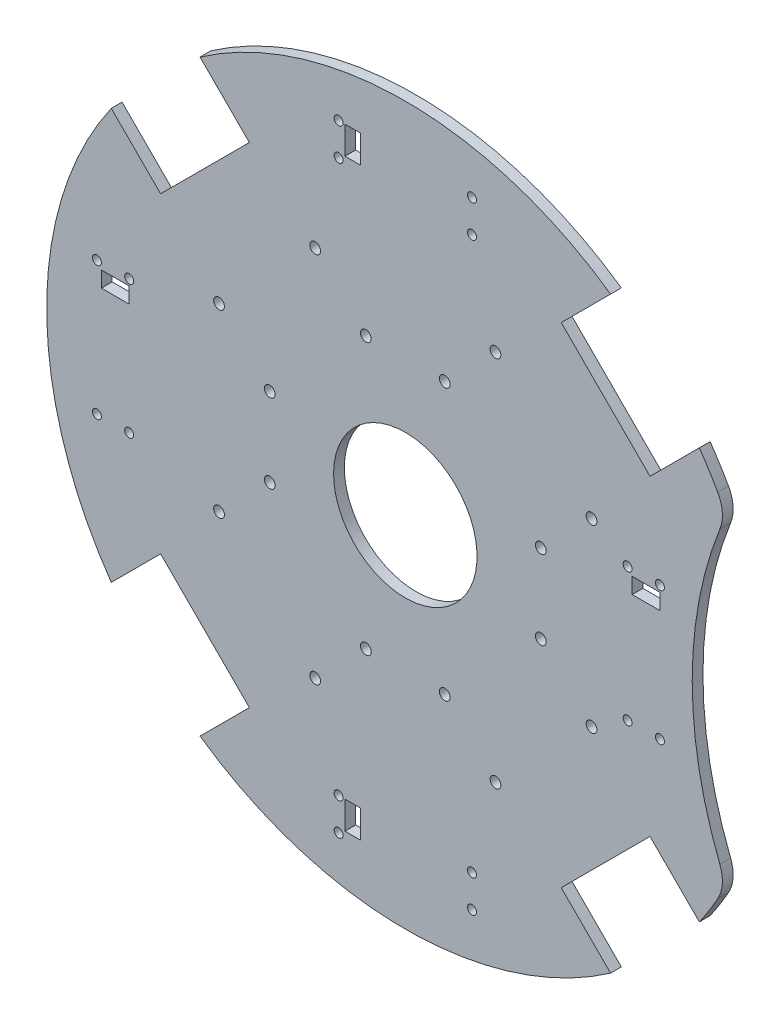
SolidWorks part; units mm, degrees
ref_plane "Alzado" through (0, 0, 0) normal (0, 0, 1) x (1, 0, 0)
ref_plane "Planta" through (0, 0, 0) normal (0, 1, 0) x (1, 0, 0)
ref_plane "Vista lateral" through (0, 0, 0) normal (1, 0, 0) x (0, 0, -1)
sketch "Croquis1" plane through (0, 0, 0) normal (0, 0, 1) x (1, 0, 0)
  circle A0 centre (0, 0) radius 100
  dimension "D1" = 200
extrude "Saliente-Extruir1" add sketch "Croquis1" along normal blind 3
sketch "Croquis3" plane through (0, 0, 3) normal (0, 0, 1) x (1, 0, 0)
  line L0 (0, 0) -> (190, 0) construction
  circle A0 centre (190, 0) radius 110
  dimension "D1" = 220
  dimension "D2" = 190
extrude "Cortar-Extruir1" cut sketch "Croquis3" against normal blind 3
fillet "Redondeo1" radius 10 2 edges at (89.4737, -44.6594, 1.5) (89.4737, 44.6594, 1.5)
sketch "Croquis4" plane through (0, 0, 3) normal (0, 0, 1) x (1, 0, 0)
  line L0 (-83.085, -58.3363) -> (-58.3363, -83.085)
  line L1 (-83.085, -58.3363) -> (-68.2358, -43.4871)
  line L2 (0, -100) -> (-100, 0) construction
  line L3 (-70.7107, -70.7107) -> (-38.5373, -38.5373) construction
  line L4 (-38.5373, -38.5373) -> (-25.1376, -51.937) construction
  line L5 (-38.5373, -38.5373) -> (-51.937, -25.1376) construction
  line L6 (-25.1376, -51.937) -> (-10.9955, -37.7949) construction
  line L7 (-51.937, -25.1376) -> (-37.7949, -10.9955) construction
  line L8 (-68.2358, -43.4871) -> (-43.4871, -68.2358)
  line L9 (-58.3363, -83.085) -> (-43.4871, -68.2358)
  line L10 (-58.3363, 83.085) -> (-43.4871, 68.2358)
  line L11 (-43.4871, 68.2358) -> (-68.2358, 43.4871)
  line L12 (-83.085, 58.3363) -> (-68.2358, 43.4871)
  line L13 (-58.3363, 83.085) -> (-83.085, 58.3363)
  line L14 (83.085, 58.3363) -> (68.2358, 43.4871)
  line L15 (68.2358, 43.4871) -> (43.4871, 68.2358)
  line L16 (58.3363, 83.085) -> (43.4871, 68.2358)
  line L17 (83.085, 58.3363) -> (58.3363, 83.085)
  line L18 (58.3363, -83.085) -> (43.4871, -68.2358)
  line L19 (43.4871, -68.2358) -> (68.2358, -43.4871)
  line L20 (83.085, -58.3363) -> (68.2358, -43.4871)
  line L21 (58.3363, -83.085) -> (83.085, -58.3363)
  arc A0 (87.1345, 49.0671) -> (87.1345, -49.0671) centre (0, 0) ccw construction
  circle A1 centre (-10.9955, 37.7949) radius 1.5
  circle A2 centre (-51.937, -25.1376) radius 1.5
  circle A3 centre (-25.1376, -51.937) radius 1.5
  circle A4 centre (-10.9955, -37.7949) radius 1.5
  circle A5 centre (-37.7949, -10.9955) radius 1.5
  circle A6 centre (-37.7949, 10.9955) radius 1.5
  circle A7 centre (-51.937, 25.1376) radius 1.5
  circle A8 centre (-25.1376, 51.937) radius 1.5
  circle A9 centre (37.7949, 10.9955) radius 1.5
  circle A10 centre (10.9955, 37.7949) radius 1.5
  circle A11 centre (25.1376, 51.937) radius 1.5
  circle A12 centre (51.937, 25.1376) radius 1.5
  circle A13 centre (10.9955, -37.7949) radius 1.5
  circle A14 centre (37.7949, -10.9955) radius 1.5
  circle A15 centre (51.937, -25.1376) radius 1.5
  circle A16 centre (25.1376, -51.937) radius 1.5
  point P43 (0, 0)
  point P60 (0, 0)
  dimension "D1" = 3
  dimension "D2" = 3
  dimension "D3" = 3
  dimension "D4" = 3
  dimension "D5" = 20
  dimension "D6" = 20
  dimension "D7" = 37.9
  dimension "D8" = 4
  dimension "D9" = 57.7005
  dimension "D10" = 35
  dimension "D11" = 21
  dimension "D12" = 35
  dimension "D13" = 17.5
  dimension "D14" = 79
  dimension "D15" = 4
extrude "Cortar-Extruir2" cut sketch "Croquis4" against normal through all
sketch "Croquis5" plane through (0, 0, 3) normal (0, 0, 1) x (1, 0, 0)
  line L0 (-100, 0) -> (-88, 0) construction
  line L1 (0, 0) -> (0, -100) construction
  line L2 (0, 0) -> (0, 100) construction
  line L3 (20.59, 88) -> (20.59, 75) construction
  line L4 (-88, 20.59) -> (-88, -20.59) construction
  line L5 (-20.59, -88) -> (20.59, -88) construction
  line L6 (-88, 20.59) -> (-75, 20.59) construction
  line L7 (-75, 20.59) -> (-75, -20.59) construction
  line L8 (-75, -20.59) -> (-88, -20.59) construction
  line L9 (20.59, 75) -> (-20.59, 75) construction
  line L10 (-20.59, 88) -> (20.59, 88) construction
  line L11 (60, 20.59) -> (60, -20.59) construction
  line L12 (-20.59, 75) -> (-20.59, 88) construction
  line L13 (60, 20.59) -> (73, 20.59) construction
  line L14 (73, 20.59) -> (73, -20.59) construction
  line L15 (73, -20.59) -> (60, -20.59) construction
  line L17 (-17.34, -77) -> (-16.84, -77) construction
  line L18 (-20.59, -88) -> (-20.59, -75) construction
  line L19 (-20.59, -75) -> (20.59, -75) construction
  line L20 (-88, 0) -> (-75, 0) construction
  line L21 (-18.59, -84.75) -> (-16.84, -84.75) construction
  line L22 (20.59, -75) -> (20.59, -88) construction
  line L23 (0, 0) -> (60, 0) construction
  line L25 (75, -20.59) -> (75, 20.59) construction
  line L26 (75, 20.59) -> (88, 20.59) construction
  line L29 (-77, 17.34) -> (-77, 16.84) construction
  line L30 (-84.75, 18.59) -> (-84.75, 16.84) construction
  line L33 (-16.84, 78.25) -> (-12.44, 78.25)
  line L34 (-84.75, 16.84) -> (-77, 16.84)
  line L35 (-84.75, 16.84) -> (-84.75, 12.44)
  line L36 (-84.75, 12.44) -> (-77, 12.44)
  line L37 (-77, 16.84) -> (-77, 12.44)
  line L38 (-16.84, 78.25) -> (-16.84, 86)
  line L39 (-16.84, 86) -> (-12.44, 86)
  line L40 (-12.44, 78.25) -> (-12.44, 86)
  line L41 (63.25, 16.84) -> (71, 16.84)
  line L42 (63.25, 16.84) -> (63.25, 12.44)
  line L43 (63.25, 12.44) -> (71, 12.44)
  line L44 (71, 16.84) -> (71, 12.44)
  line L45 (-16.84, -84.75) -> (-12.44, -84.75)
  line L46 (-16.84, -84.75) -> (-16.84, -77)
  line L47 (-16.84, -77) -> (-12.44, -77)
  line L48 (-12.44, -84.75) -> (-12.44, -77)
  circle A0 centre (-86, 18.59) radius 1.25
  arc A1 (-57.2451, -81.9939) -> (57.2451, -81.9939) centre (0, 0) ccw construction
  arc A2 (57.2451, 81.9939) -> (-57.2451, 81.9939) centre (0, 0) ccw construction
  circle A3 centre (-77, 18.59) radius 1.25
  arc A4 (-81.9939, 57.2451) -> (-81.9939, -57.2451) centre (0, 0) ccw construction
  circle A5 centre (-77, -18.59) radius 1.25
  circle A6 centre (-86, -18.59) radius 1.25
  circle A7 centre (18.59, 77) radius 1.25
  circle A8 centre (18.59, 86) radius 1.25
  circle A9 centre (-18.59, 86) radius 1.25
  circle A10 centre (-18.59, 77) radius 1.25
  circle A11 centre (62, 18.59) radius 1.25
  circle A12 centre (71, 18.59) radius 1.25
  circle A13 centre (62, -18.59) radius 1.25
  circle A14 centre (71, -18.59) radius 1.25
  circle A15 centre (-18.59, -77) radius 1.25
  circle A16 centre (-18.59, -86) radius 1.25
  circle A17 centre (18.59, -86) radius 1.25
  circle A18 centre (18.59, -77) radius 1.25
  point P38 (0, 0)
  point P81 (0, 0)
  dimension "D3" = 2.5
  dimension "D4" = 4.4
  dimension "D5" = 2
  dimension "D6" = 2.5
  dimension "D7" = 2
  dimension "D8" = 2
  dimension "D11" = 2.5
  dimension "D12" = 2.5
  dimension "D13" = 2.5
  dimension "D14" = 2.5
  dimension "D15" = 2
  dimension "D16" = 2
  dimension "D17" = 2
  dimension "D18" = 2
  dimension "D20" = 2
  dimension "D21" = 2
  dimension "D22" = 2
  dimension "D23" = 2
  dimension "D24" = 2
  dimension "D25" = 3.25
  dimension "D10" = 4.4
  dimension "D1" = 4
  dimension "D2" = 60
  dimension "D9" = 13
  dimension "D19" = 13
  dimension "D27" = 3.25
  dimension "D29" = 1.75
  dimension "D30" = 0.5
  dimension "D31" = 1.75
  dimension "D32" = 0.5
  dimension "D33" = 4.4
  dimension "D34" = 4.4
extrude "Cortar-Extruir3" cut sketch "Croquis5" against normal through all
sketch "Croquis6" plane through (0, 0, 0) normal (0, 0, -1) x (-1, 0, 0)
  circle A0 centre (0, 0) radius 20
  dimension "D1" = 40
extrude "Cortar-Extruir4" cut sketch "Croquis6" against normal through all
